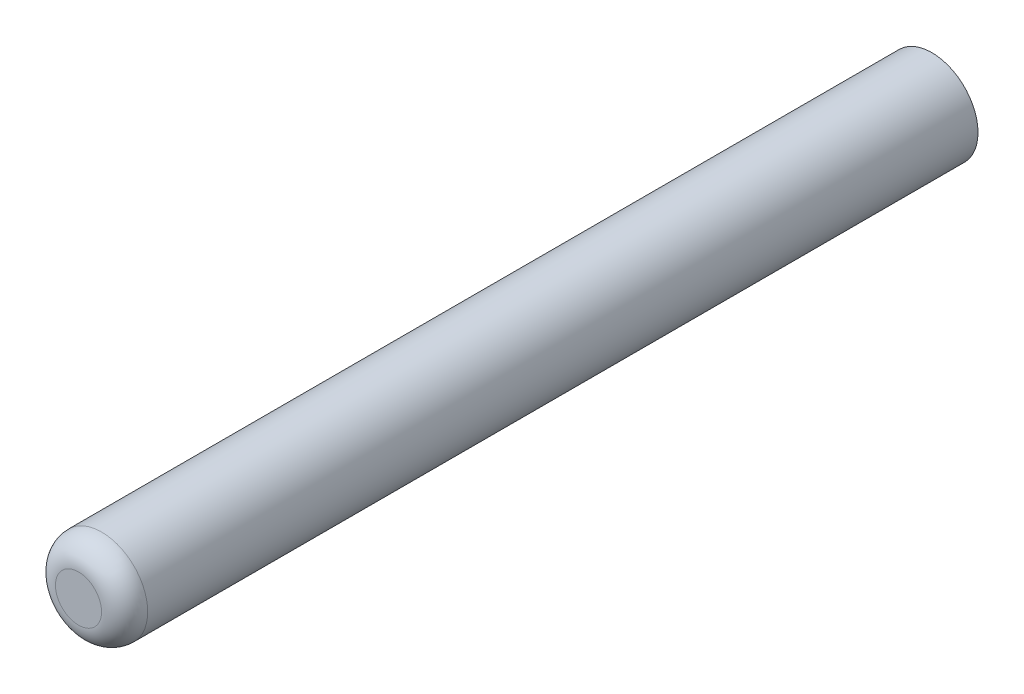
SolidWorks part; units mm, degrees
ref_plane "Front Plane" through (0, 0, 0) normal (0, 0, 1) x (1, 0, 0)
ref_plane "Top Plane" through (0, 0, 0) normal (0, 1, 0) x (1, 0, 0)
ref_plane "Right Plane" through (0, 0, 0) normal (1, 0, 0) x (0, 0, -1)
sketch "Sketch1" plane through (0, 0, 0) normal (0, 0, 1) x (1, 0, 0)
  circle A0 centre (-33.0532, 3.4901) radius 2
extrude "Boss-Extrude1" add sketch "Sketch1" along normal blind 37
fillet "Fillet1" radius 1 1 edges at (-31.0532, 3.4901, 37)
